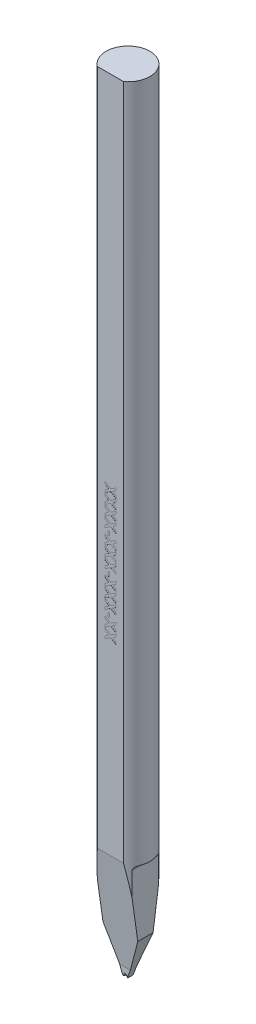
SolidWorks part; units mm, degrees
ref_plane "Ebene vorne" through (0, 0, 0) normal (0, 0, 1) x (1, 0, 0)
ref_plane "Ebene oben" through (0, 0, 0) normal (0, 1, 0) x (1, 0, 0)
ref_plane "Ebene rechts" through (0, 0, 0) normal (1, 0, 0) x (0, 0, -1)
sketch "sketch_TL_cutting" plane through (0, 0, 0) normal (0, 1, 0) x (1, 0, 0)
  circle A0 centre (0, 0) radius 1.9977
extrude "TL_cutting" add sketch "sketch_TL_cutting" along normal blind 72.009
sketch "sketch_TDF_grinding" plane through (0, 0, 0) normal (0, 1, 0) x (1, 0, 0)
  line L0 (0, 0) -> (0, -1.6015) construction
  line L1 (-2.0077, -5.6169) -> (2.0077, -5.6169)
  line L2 (-2.0077, -5.6169) -> (-2.0077, -1.6015)
  line L3 (-2.0077, -1.6015) -> (2.0077, -1.6015)
  line L4 (2.0077, -5.6169) -> (2.0077, -1.6015)
  circle A1 centre (0, 0) radius 1.9977 construction
  point P9 (0, -5.6169)
  dimension "TD_2Offset_X" = 4.0154
  dimension "TD_2Offset_Z" = 4.0154
extrude "TDF_grinding" cut sketch "sketch_TDF_grinding" along normal through all
sketch "sketch_engraving" plane through (0, 0, 1.6015) normal (0, 0, 1) x (1, 0, 0)
  line L0 (1.1942, 72.009) -> (-1.1942, 72.009) construction
  line L6 (-1.1942, 0) -> (1.1942, 0) construction
  line L7 (0, 0) -> (0, 39.605) construction
  line L8 (-0.5, 39.605) -> (-0.5, 0) construction
  text T0 "XXXX-XXX-XXX-XX" font "Arial" height 1
  dimension "D2" = 0.5
  dimension "EngravingStart" = 32.404
extrude "engraving" cut sketch "sketch_engraving" against normal blind 0.005
sketch "sketch_VW_VR_grinding" plane through (0, 0, 0) normal (0, 0, 1) x (1, 0, 0)
  line L0 (-1.59, -0.01) -> (-1.59, 9.682)
  line L1 (1.59, -0.01) -> (1.59, 9.682)
  line L2 (-1.59, 0) -> (1.59, 0) construction
  line L3 (-2.0077, 10) -> (-1.908, 10)
  line L4 (1.908, 10) -> (2.0077, 10)
  line L5 (-2.0077, 10) -> (-2.0077, -0.01)
  line L6 (-2.0077, -0.01) -> (-1.59, -0.01)
  line L7 (1.59, -0.01) -> (2.0077, -0.01)
  line L8 (2.0077, -0.01) -> (2.0077, 10)
  line L9 (-1.908, 10) -> (-1.908, 9.682) construction
  line L10 (-1.59, 9.682) -> (-1.908, 9.682) construction
  line L11 (1.59, 9.682) -> (1.908, 9.682) construction
  line L12 (1.908, 10) -> (1.908, 9.682) construction
  arc A0 (-1.908, 10) -> (-1.59, 9.682) centre (-1.908, 9.682) cw
  arc A2 (1.59, 9.682) -> (1.908, 10) centre (1.908, 9.682) cw
  dimension "D1" = 0.01
  dimension "D4" = 4.0154
extrude "VW_VR_grinding" cut sketch "sketch_VW_VR_grinding" against normal blind 2.0077 and the other way blind 2.0077
sketch "sketch_ISA_grinding" plane through (0, 0, 0) normal (0, 0, 1) x (1, 0, 0)
  line L0 (-0.1994, 0) -> (-2.0077, 4.9683)
  line L4 (2.0077, 4.9683) -> (0.1994, 0)
  line L5 (0.1994, 0) -> (-0.1994, 0)
  line L6 (0, 0) -> (0, 30.49) construction
  line L7 (-2.0077, 4.9683) -> (-2.0077, -0.01)
  line L12 (-2.0077, -0.01) -> (2.0077, -0.01)
  line L13 (2.0077, -0.01) -> (2.0077, 4.9683)
  line L14 (-1.59, -0.01) -> (-1.59, 9.682) construction
  point P3 (-1.59, 3.8208)
  dimension "ISA" = 40
  dimension "TD_2Offset" = 4.0154
  dimension "Offset" = 0.01
extrude "ISA_grinding" cut sketch "sketch_ISA_grinding" against normal blind 2.0077 and the other way blind 2.0077
sketch "sketch_pre_FRX_BRX" plane through (0, 0, 0) normal (1, 0, 0) x (0, 0, -1)
  line L0 (1.9977, -0.01) -> (1.9977, 3.9152) construction
  line L1 (-1.6015, -0.01) -> (-1.6015, 0.7799) construction
  line L2 (-0.2705, -0.01) -> (-0.2705, 0.7799)
  line L3 (-0.2705, 0.7799) -> (-2.0077, 0.7799)
  line L4 (-2.0077, 0.7799) -> (-2.0077, -0.01)
  line L5 (-2.0077, -0.01) -> (-0.2705, -0.01)
  line L6 (0.2705, -0.01) -> (0.2705, 0.7799)
  line L7 (0.2705, 0.7799) -> (2.0077, 0.7799)
  line L8 (2.0077, 0.7799) -> (2.0077, -0.01)
  line L9 (2.0077, -0.01) -> (0.2705, -0.01)
  dimension "D3" = 0.01
  dimension "D4" = 0.7899
  dimension "D5" = 4.0154
  dimension "D6" = 0.541
  dimension "D2" = 0.01
  dimension "D7" = 2.2682
extrude "pre_FRX_BRX" cut sketch "sketch_pre_FRX_BRX" against normal blind 2.0077 and the other way blind 2.0077
sketch "sketch_contour_V-Groove" plane through (0, 0, 0) normal (1, 0, 0) x (0, 0, -1)
  line L0 (-1.6015, 0.1118) -> (0, 0.1118)
  line L1 (0, 0.1118) -> (1.9977, 0.1118)
  line L2 (1.9977, -0.8411) -> (1.9977, 1.3178) construction
  line L3 (-1.6015, -0.9209) -> (-1.6015, 1.9363) construction
  line L4 (-1.6015, 0) -> (1.9977, 0) construction
  line L5 (0.2705, 0) -> (0.2705, 0.1118) construction
  line L6 (-0.2705, 0) -> (-0.2705, 0.1118) construction
  dimension "D1" = 0
ref_plane "front" through (0, 0, 1.6015) normal (0, 0, 1) x (1, 0, 0)
ref_plane "back" through (0, 0, -1.9977) normal (0, 0, 1) x (1, 0, 0)
sketch "sketch_section_V-Groove" plane through (0, 0, 1.6015) normal (0, 0, 1) x (1, 0, 0)
  line L0 (-1.2395, -1.1176) -> (-0.0173, 0.1046)
  line L2 (0.0173, 0.1046) -> (1.2395, -1.1176)
  line L3 (-1.2395, -1.1176) -> (1.2395, -1.1176)
  line L4 (0, -1.1176) -> (0, 0.1118) construction
  line L5 (-0.1219, 0) -> (0.1219, 0) construction
  arc A0 (0.0173, 0.1046) -> (-0.0173, 0.1046) centre (0, 0.0872) ccw
  dimension "GA" = 90
sweep "V-Groove_EDM" cut profiles "sketch_section_V-Groove" path "sketch_contour_V-Groove"
fillet "FR_EDM" radius 0.2007 3 edges at (0.0696, 0.0523, 0.2705) (0, 0.1118, 0.2705) (-0.0696, 0.0523, 0.2705)
fillet "BR_EDM" radius 0.0991 3 edges at (0.0696, 0.0523, -0.2705) (0, 0.1118, -0.2705) (-0.0696, 0.0523, -0.2705)
sketch "sketch_FA_BA_grinding" plane through (0, 0, 0) normal (1, 0, 0) x (0, 0, -1)
  line L2 (2.9977, 20.195) -> (2.9977, -0.1)
  line L3 (2.9977, -0.1) -> (0.2705, -0.1)
  line L5 (0.2705, -0.1) -> (0.2705, 0.7899)
  line L6 (0.2705, 0.7899) -> (2.9977, 20.195)
  line L7 (1.9977, -0.1) -> (1.9977, 13.0796) construction
  line L8 (-1.6015, 10.2602) -> (-1.6015, -0.1) construction
  line L9 (-3.2182, 21.764) -> (-0.2705, 0.7899)
  line L10 (-0.2705, 0.7899) -> (-0.2705, -0.1)
  line L11 (-0.2705, -0.1) -> (-3.2182, -0.1)
  line L12 (-3.2182, -0.1) -> (-3.2182, 21.764)
  line L13 (-0.2705, 0.7899) -> (0.2705, 0.7899) construction
  dimension "D4" = 1
  dimension "D1" = 0.1
  dimension "FA" = 8
  dimension "BA" = 8
extrude "FA_BA_grinding" cut sketch "sketch_FA_BA_grinding" against normal blind 2.0077 and the other way blind 2.0077
sketch "sketch_groove_dimensions" plane through (0, 0, 0) normal (1, 0, 0) x (0, 0, -1)
  line L0 (-0.0698, 0.1118) -> (0.1715, 0.1118)
  line L1 (-0.2705, 0) -> (-0.2705, 0.3124) construction
  line L2 (1.9977, 0) -> (1.9977, 0.4166) construction
  line L3 (0.2705, 0) -> (0.2705, 0.2108) construction
  line L4 (-1.6015, 0) -> (-1.6015, 0.3999) construction
  arc A0 (0.1715, 0.1118) -> (0.2705, 0.2108) centre (0.1715, 0.2108) ccw
  arc A1 (-0.0698, 0.1118) -> (-0.2705, 0.3124) centre (-0.0698, 0.3124) cw
equation "\"_Offset\"=0.01mm"
equation "\"TL\"=72.009mm"
equation "\"TD\"=3.99542mm"
equation "\"TDF\"=3.59918mm"
equation "\"BA\"=8deg"
equation "\"ISA\"=40deg"
equation "\"FA\"=8deg"
equation "\"GR\"=0.0254mm"
equation "\"GA\"=90deg"
equation "\"GD\"=0.11176mm"
equation "\"FL\"=0.54102mm"
equation "\"F\"=0.23876mm"
equation "\"FX\"=0mm"
equation "\"B\"=0.24384mm"
equation "\"VW\"=3.18008mm"
equation "\"cleaned_VR\"= IIF ( \"VR\" > 0 , \"VR\" , \"E\" - \"_Offset\" )"
equation "\"cleaned_VW\"= IIF ( \"VW\" > 0 , \"VW\" , \"TD\" - \"_Offset\" )"
equation "\"back_edge\"= \"TD\" / 2 - \"X\""
equation "\"side_edge_Offset\"= \"TD\" / 2 + \"_Offset\""
equation "\"TD@sketch_TL_cutting\"=\"TD\""
equation "\"TL@TL_cutting\"=\"TL\""
equation "\"TDF@sketch_TDF_grinding\"=\"TDF\""
equation "\"TD_2Offset_X@sketch_TDF_grinding\"=\"TD\"+2*\"_Offset\""
equation "\"TD_2Offset_Z@sketch_TDF_grinding\"=\"TD\"+2*\"_Offset\""
equation "\"TL_Offset\"= \"TL\" + \"_Offset\""
equation "\"ISA@sketch_ISA_grinding\"=\"ISA\""
equation "\"W@sketch_ISA_grinding\"=\"W\""
equation "\"TD_2Offset@sketch_ISA_grinding\"=\"TD\"+2*\"_Offset\""
equation "\"Offset@sketch_ISA_grinding\"=\"_Offset\""
equation "\"05TD_Offset_posZ@ISA_grinding\"=\"side_edge_Offset\""
equation "\"05TD_Offset_negZ@ISA_grinding\"=\"side_edge_Offset\""
equation "\"E\"=0.78994mm"
equation "\"cleaned_X\"= IIF ( \"X\" > 0 , \"X\" , \"TD\" / 2 - \"FL\" / 2 )"
equation "\"FR\"=0.20066mm"
equation "\"BR\"=0.09906mm"
equation "\"D1\"= \"side_edge_Offset\""
equation "\"D2\"= \"side_edge_Offset\""
equation "\"TDF@sketch_FA_BA_grinding\" = \"TDF\""
equation "\"FL@sketch_FA_BA_grinding\"=\"FL\""
equation "\"E@sketch_FA_BA_grinding\" = \"E\""
equation "\"D1@FA_BA_grinding\"=\"side_edge_Offset\""
equation "\"D2@FA_BA_grinding\"=\"side_angle_Offset\""
equation "\"10GD@sketch_section_V-Groove\" = 10 * \"GD\""
equation "\"GA@sketch_section_V-Groove\" = \"GA\""
equation "\"GD@sketch_section_V-Groove\" = \"GD\""
equation "\"B@sketch_section_V-Groove\" = \"B\""
equation "\"GD@sketch_contour_V-Groove\" = \"GD\""
equation "\"cleaned_FRX\"= IIF ( \"FRX\" > 0 , \"FRX\" , \"FR\" )"
equation "\"cleaned_BRX\"= IIF ( \"BRX\" > 0 , \"BRX\" , \"BR\" )"
equation "\"FL_groove_angle\"=0deg"
equation "\"D3@sketch_pre_FRX_BRX\" = \"_Offset\""
equation "\"D4@sketch_pre_FRX_BRX\" = \"E\""
equation "\"D5@sketch_pre_FRX_BRX\" = 2 * \"side_edge_Offset\""
equation "\"D6@sketch_pre_FRX_BRX\" = \"FL\" + ( \"FR\" - \"cleaned_FRX\" ) + ( \"BR\" - \"cleaned_BRX\" )"
equation "\"TD/2@sketch_pre_FRX_BRX\" = \"TD\" / 2"
equation "\"TDF@sketch_pre_FRX_BRX\" = \"TDF\""
equation "\"D2@sketch_pre_FRX_BRX\" = \"_Offset\""
equation "\"D1@pre_FRX_BRX\" = \"side_edge_Offset\""
equation "\"D2@pre_FRX_BRX\" = \"side_edge_Offset\""
equation "\"D1@BR_EDM\"=\"BR\""
equation "\"TD/2@sketch_FA_BA_grinding\" = \"TD\" / 2"
equation "\"TD/2@sketch_contour_V-Groove\" = \"TD\" / 2"
equation "\"TDF@sketch_contour_V-Groove\" = \"TDF\""
equation "\"D1@sketch_contour_V-Groove\"=\"FL_groove_angle\""
equation "\"FL@sketch_contour_V-Groove\"=\"FL\""
equation "\"FL/2@sketch_contour_V-Groove\" = \"FL\" / 2"
equation "\"D1@FR_EDM\"=\"FR\""
equation "\"D1@sketch_VW_VR_grinding\" = \"_Offset\""
equation "\"D4@sketch_VW_VR_grinding\" = 2 * \"side_edge_Offset\""
equation "\"VR@sketch_VW_VR_grinding\" = \"cleaned_VR\""
equation "\"VW@sketch_VW_VR_grinding\"=\"cleaned_VW\""
equation "\"D1@VW_VR_grinding\" = \"side_edge_Offset\""
equation "\"D2@VW_VR_grinding\" = \"side_edge_Offset\""
equation "\"X\"=0.94996mm"
equation "\"VR\"=9.99998mm"
equation "\"W\"=0.39878mm"
equation "\"VW_radius\"= \"cleaned_VW\" / 10"
equation "\"VW_radius_cleaned\"= IIF ( \"VW\" > 0 , \"VW_radius\" , \"_Offset\" / 2 )"
equation "\"D2@sketch_VW_VR_grinding\"=\"VW_radius_cleaned\""
equation "\"FRX\"=0mm"
equation "\"BRX\"=0mm"
equation "\"FA@sketch_FA_BA_grinding\" = \"FA\""
equation "\"D4@sketch_FA_BA_grinding\"=\"_Offset\"*100"
equation "\"BA@sketch_FA_BA_grinding\" = \"BA\""
equation "\"D1@sketch_groove_dimensions\" = \"TD\" / 2"
equation "\"FL@sketch_groove_dimensions\" = \"FL\""
equation "\"FR@sketch_groove_dimensions\" = \"FR\""
equation "\"BR@sketch_groove_dimensions\" = \"BR\""
equation "\"FRX@sketch_groove_dimensions\" = \"cleaned_FRX\""
equation "\"BRX@sketch_groove_dimensions\" = \"cleaned_BRX\""
equation "\"GD@sketch_groove_dimensions\" = \"GD\""
equation "\"cleaned_FX\"= IIF ( \"FX\" > 0 , \"FX\" , \"TDF\" - ( \"TD\" + \"FL\" ) / 2 )"
equation "\"D7@sketch_pre_FRX_BRX\"=\"TDF\"-\"cleaned_FX\"-(\"FR\"-\"cleaned_FRX\")"
equation "\"FX@sketch_contour_V-Groove\" = \"cleaned_FX\""
equation "\"FX@sketch_FA_BA_grinding\" = \"cleaned_FX\""
equation "\"TDF@sketch_groove_dimensions\" = \"TDF\""
equation "\"FX@sketch_groove_dimensions\" = \"cleaned_FX\""
equation "\"EngravingStart\" = \"TL\" * 0.45"
equation "\"EngravingStart@sketch_engraving\" = \"EngravingStart\""
